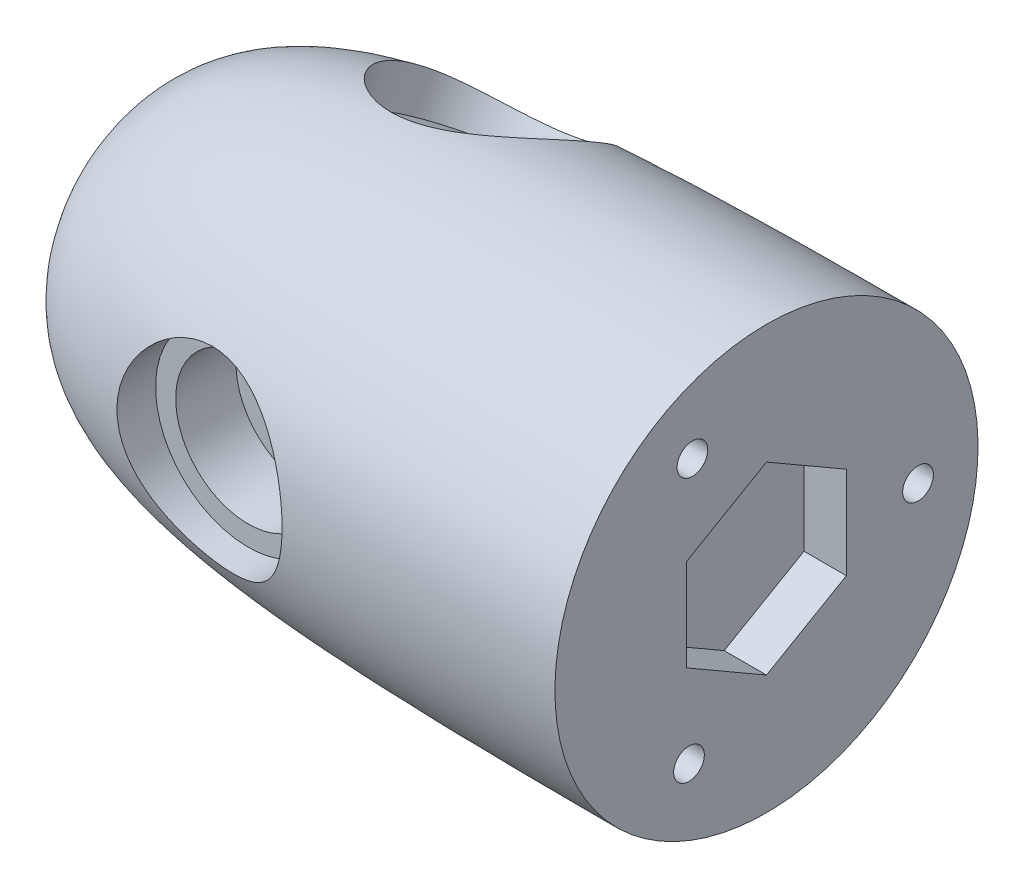
SolidWorks part; units mm, degrees
material "ABS"
ref_plane "Front Plane" through (0, 0, 0) normal (0, 0, 1) x (1, 0, 0)
ref_plane "Top Plane" through (0, 0, 0) normal (0, 1, 0) x (1, 0, 0)
ref_plane "Right Plane" through (0, 0, 0) normal (1, 0, 0) x (0, 0, -1)
sketch "Sketch1" plane through (0, 0, 0) normal (0, 0, 1) x (1, 0, 0)
  line L0 (0, 0) -> (-6, 0)
  line L1 (0, 0) -> (0, 2)
  line L2 (-6, 0) -> (-6, 3.0411) construction
  line L3 (0, 2) -> (-5.0439, 2) construction
  spline S0 degree 3 poles (-6, 0) (-6, 1.7778) (-4.7159, 2) (0, 2) knots 0 0 0 0 1 1 1 1
  dimension "D1" = 2
  dimension "D2" = 6
revolve "Revolve1" add sketch "Sketch1" angle 360 about L0
ref_plane "Plane4" through (0, 0, 2) normal (0, 0, 1) x (1, 0, 0)
sketch "Sketch3" plane through (0, 0, 2) normal (0, 0, 1) x (1, 0, 0)
  line L0 (0, 0) -> (-5.879, 0) construction
  line L1 (0, -2) -> (0, 2) construction
  circle A0 centre (-3.5, 0) radius 0.685
  dimension "D1" = 1.37
  dimension "D2" = 3.5
extrude "Cut-Extrude1" cut sketch "Sketch3" against normal blind 1.17
sketch "Sketch4" plane through (0, 0, 2) normal (0, 0, 1) x (1, 0, 0)
  line L0 (0, -2) -> (0, 2) construction
  circle A0 centre (-3.5, 0) radius 0.875
  dimension "D1" = 1.75
  dimension "D2" = 3.5
extrude "Cut-Extrude2" cut sketch "Sketch4" against normal blind 0.6
pattern_circular "CirPattern1" count 3 every 120 about axis through (0, 0, 0) along (1, 0, 0) of "Cut-Extrude1", "Cut-Extrude2"
scale "Scale1" scale about centroid uniform scaling yes scale factor 10
sketch "Sketch7" plane through (22.6252, 0, 0) normal (1, 0, 0) x (0, 0, -1)
  line L1 (0, 8.718) -> (-7.55, 4.359)
  line L2 (-7.55, 4.359) -> (-7.55, -4.359)
  line L3 (-7.55, -4.359) -> (0, -8.718)
  line L4 (0, -8.718) -> (7.55, -4.359)
  line L5 (7.55, -4.359) -> (7.55, 4.359)
  line L6 (7.55, 4.359) -> (0, 8.718)
  circle A0 centre (0, 0) radius 7.55 construction
  dimension "D1" = 15.1
extrude "Cut-Extrude3" cut sketch "Sketch7" against normal blind 4
sketch "Sketch8" plane through (22.6252, 0, 0) normal (1, 0, 0) x (0, 0, -1)
  line L0 (0, 0) -> (-24.3265, 0) construction
  line L1 (0, 0) -> (0, 23.0414) construction
  circle A0 centre (-7, 12.5) radius 1.45
  circle A1 centre (14.3253, -0.1878) radius 1.45
  circle A2 centre (-7.3253, -12.3122) radius 1.45
  point P13 (0, 0)
  dimension "D4" = 2.9
  dimension "D1" = 12.5
  dimension "D2" = 7
  dimension "D3" = 3
extrude "Cut-Extrude4" cut sketch "Sketch8" against normal blind 10
